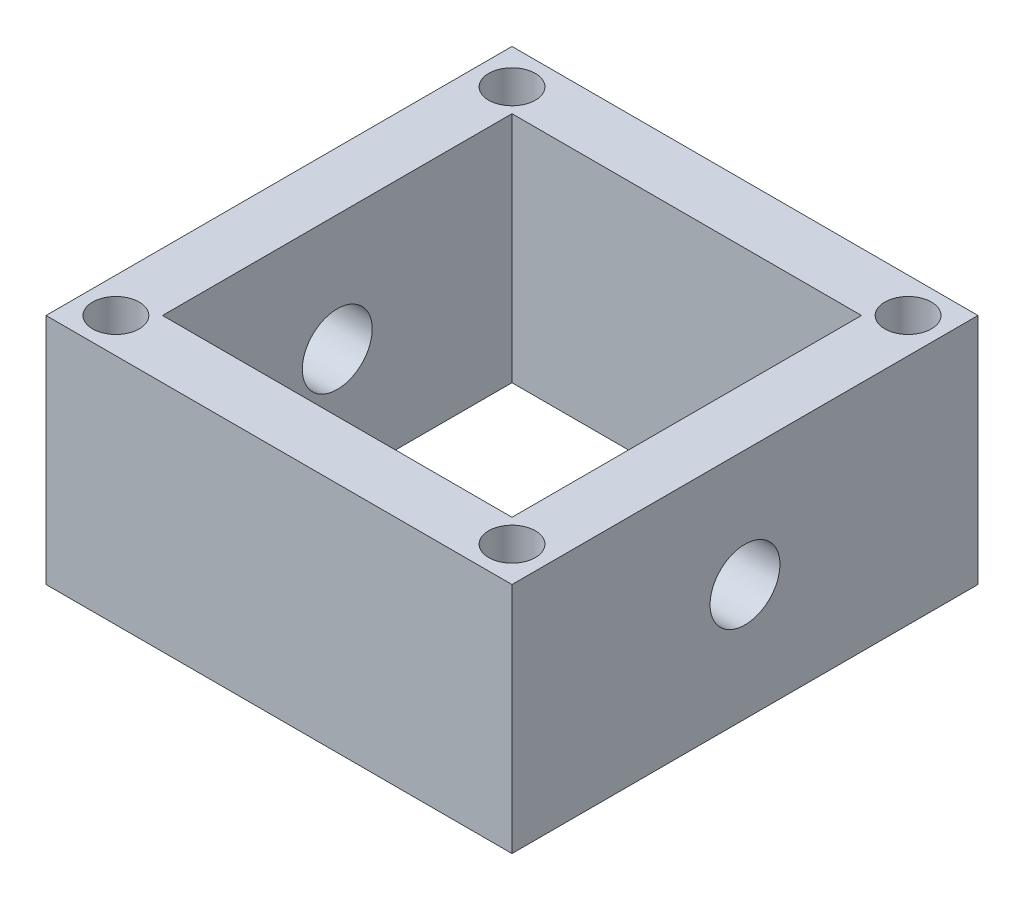
SolidWorks part; units mm, degrees
ref_plane "Front Plane" through (0, 0, 0) normal (0, 0, 1) x (1, 0, 0)
ref_plane "Top Plane" through (0, 0, 0) normal (0, 1, 0) x (1, 0, 0)
ref_plane "Right Plane" through (0, 0, 0) normal (1, 0, 0) x (0, 0, -1)
sketch "Sketch1" plane through (0, 0, 0) normal (0, 1, 0) x (1, 0, 0)
  line L1 (-7.5, 7.5) -> (7.5, 7.5)
  line L2 (-7.5, 7.5) -> (-7.5, -7.5)
  line L3 (-7.5, -7.5) -> (7.5, -7.5)
  line L4 (7.5, 7.5) -> (7.5, -7.5)
  line L5 (-7.5, 7.5) -> (7.5, -7.5) construction
  line L6 (-7.5, -7.5) -> (7.5, 7.5) construction
  line L7 (-10, 10) -> (10, 10)
  line L8 (-10, 10) -> (-10, -10)
  line L9 (-10, -10) -> (10, -10)
  line L10 (10, 10) -> (10, -10)
  line L11 (-10, 10) -> (10, -10) construction
  line L12 (-10, -10) -> (10, 10) construction
  point P0 (0, 0)
  point P6 (0, 0)
  dimension "D1" = 15
  dimension "D2" = 15
  dimension "D3" = 20
  dimension "D4" = 20
extrude "Boss-Extrude1" add sketch "Sketch1" along normal blind 10
sketch "Sketch2" plane through (-10, 0, 0) normal (-1, 0, 0) x (0, 0, 1)
  line L0 (-10, 5) -> (10, 5) construction
  line L2 (-10, 10) -> (-10, 0) construction
  line L3 (10, 10) -> (10, 0) construction
  circle A0 centre (0, 5) radius 1.5
  point P3 (0, 4.2553)
  point P10 (0, 5)
  dimension "D1" = 3
extrude "Cut-Extrude1" cut sketch "Sketch2" against normal through all
sketch "Sketch3" plane through (0, 10, 0) normal (0, 1, 0) x (1, 0, 0)
  line L0 (10, 10) -> (-10, 10) construction
  line L1 (-10, 10) -> (-10, -10) construction
  line L2 (10, -10) -> (10, 10) construction
  line L3 (-10, -10) -> (10, -10) construction
  circle A0 centre (-8.5, 8.5) radius 1
  circle A1 centre (8.5, 8.5) radius 1
  circle A2 centre (8.5, -8.5) radius 1
  circle A3 centre (-8.5, -8.5) radius 1
  point P8 (0, 0)
  point P9 (0, 0)
  point P10 (0, 0)
  point P11 (0, 0)
  point P12 (0, 0)
  point P13 (-13.9342, 12.6492)
  point P14 (-13.4122, 12.4886)
  point P15 (12.6894, -12.6091)
  dimension "D3" = 2
  dimension "D5" = 2
  dimension "D6" = 2
  dimension "D7" = 2
  dimension "D1" = 1.5
  dimension "D2" = 1.5
  dimension "D4" = 1.5
  dimension "D8" = 1.5
extrude "Cut-Extrude2" cut sketch "Sketch3" against normal blind 6
